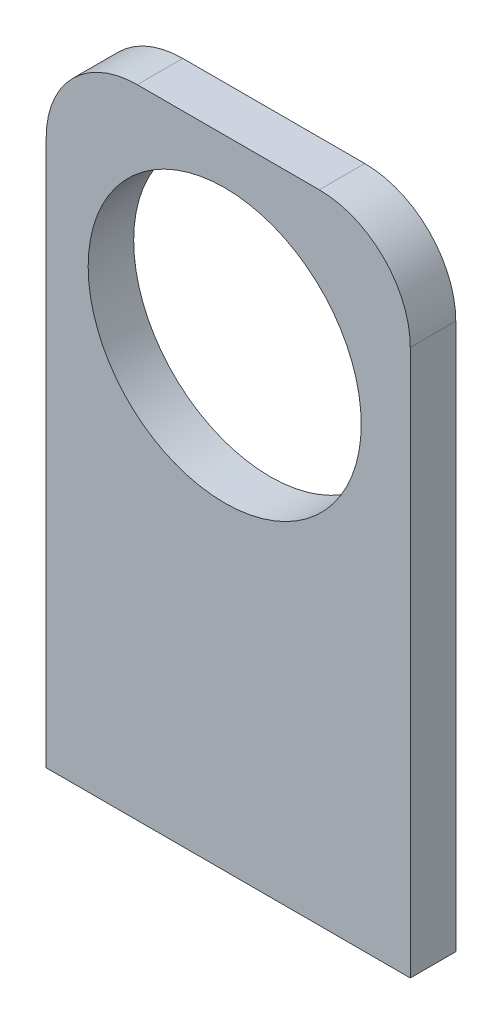
SolidWorks part; units mm, degrees
ref_plane "Front Plane" through (0, 0, 0) normal (0, 0, 1) x (1, 0, 0)
ref_plane "Top Plane" through (0, 0, 0) normal (0, 1, 0) x (1, 0, 0)
ref_plane "Right Plane" through (0, 0, 0) normal (1, 0, 0) x (0, 0, -1)
sketch "Sketch1" plane through (0, 0, 0) normal (0, 0, 1) x (1, 0, 0)
  line L1 (-0.4175, -43.3804) -> (24.9825, -43.3804)
  line L2 (-0.4175, -43.3804) -> (-0.4175, 1.0696)
  line L3 (-0.4175, 1.0696) -> (24.9825, 1.0696)
  line L4 (24.9825, -43.3804) -> (24.9825, 1.0696)
  circle A0 centre (12.035, -11.6304) radius 9.525
  dimension "D4" = 19.05
  dimension "D1" = 25.4
  dimension "D2" = 44.45
  dimension "D3" = 31.75
extrude "Boss-Extrude1" add sketch "Sketch1" along normal blind 3.175
fillet "Fillet1" radius 6.35 2 edges at (-0.4175, 1.0696, 1.5875) (24.9825, 1.0696, 1.5875)
